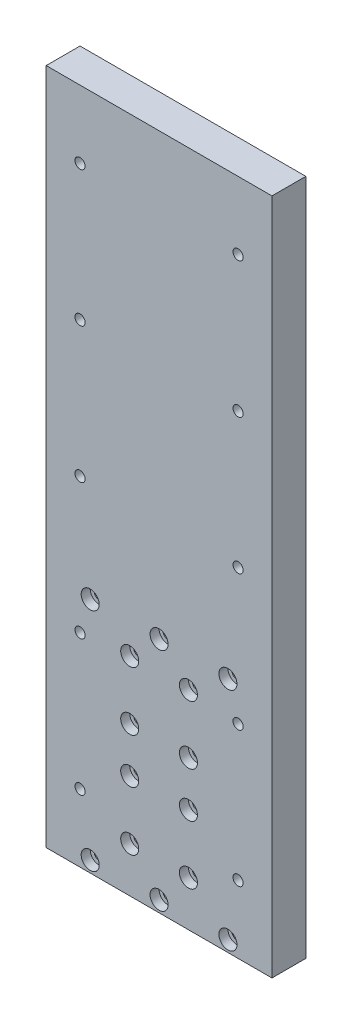
SolidWorks part; units mm, degrees
ref_plane "Piano frontale" through (0, 0, 0) normal (0, 0, 1) x (1, 0, 0)
ref_plane "Piano superiore" through (0, 0, 0) normal (0, 1, 0) x (1, 0, 0)
ref_plane "Piano destro" through (0, 0, 0) normal (1, 0, 0) x (0, 0, -1)
sketch "Schizzo1" plane through (0, 0, 0) normal (0, 0, 1) x (1, 0, 0)
  line L1 (0, 0) -> (100, 0)
  line L2 (0, 0) -> (0, 300)
  line L3 (0, 300) -> (100, 300)
  line L4 (100, 0) -> (100, 300)
  dimension "D1" = 100
  dimension "D2" = 300
extrude "Estrusione-Estrusione1" add sketch "Schizzo1" against normal blind 15
sketch "Schizzo2" plane through (0, 0, 0) normal (0, 0, 1) x (1, 0, 0)
  line L0 (0, 0) -> (104.4353, 0) construction
  line L1 (0, 5) -> (104.4353, 5) construction
  line L2 (23.1648, 20) -> (74.0129, 20) construction
  line L3 (23.1648, 46) -> (74.0129, 46) construction
  line L4 (23.1648, 66) -> (74.0129, 66) construction
  line L5 (23.1648, 92) -> (74.0129, 92) construction
  line L6 (6.7858, 105) -> (86.7249, 105) construction
  line L11 (0, 92) -> (144.5719, 92) construction
  line L12 (0, 66) -> (144.5719, 66) construction
  line L14 (50, 0) -> (50, 300) construction
  line L15 (0, 46) -> (144.5719, 46) construction
  line L17 (63, 0) -> (63, 105) construction
  line L19 (0, 20) -> (144.5719, 20) construction
  line L20 (0, 5) -> (144.5719, 5) construction
  line L21 (0, 0) -> (144.5719, 0) construction
  line L22 (0, 105) -> (144.5719, 105) construction
  line L23 (100, 300) -> (0, 300) construction
  circle A0 centre (19.5, 105) radius 2.25
  circle A1 centre (19.5, 5) radius 2.25
  circle A2 centre (37, 20) radius 2.25
  circle A3 centre (37, 46) radius 2.25
  circle A4 centre (37, 66) radius 2.25
  circle A5 centre (37, 92) radius 2.25
  circle A6 centre (50, 105) radius 2.25
  circle A7 centre (50, 5) radius 2.25
  circle A8 centre (63, 92) radius 2.25
  circle A9 centre (63, 66) radius 2.25
  circle A10 centre (63, 46) radius 2.25
  circle A11 centre (63, 20) radius 2.25
  circle A12 centre (80.5, 5) radius 2.25
  circle A13 centre (80.5, 105) radius 2.25
  dimension "D7" = 4.5
  dimension "D8" = 13
  dimension "D2" = 26
  dimension "D3" = 26
  dimension "D4" = 20
  dimension "D5" = 20
  dimension "D9" = 30.5
  dimension "D10" = 30.5
  dimension "D1" = 5
  dimension "D6" = 105
extrude "Taglio-Estrusione1" cut sketch "Schizzo2" against normal through all
sketch "Schizzo4" plane through (0, 0, 0) normal (0, 0, 1) x (1, 0, 0)
  circle A0 centre (19.5, 105) radius 4
  circle A1 centre (50, 105) radius 4
  circle A2 centre (80.5, 105) radius 4
  circle A3 centre (37, 92) radius 4
  circle A4 centre (63, 92) radius 4
  circle A5 centre (37, 66) radius 4
  circle A6 centre (63, 66) radius 4
  circle A7 centre (37, 46) radius 4
  circle A8 centre (63, 46) radius 4
  circle A9 centre (19.5, 5) radius 4
  circle A10 centre (37, 20) radius 4
  circle A11 centre (63, 20) radius 4
  circle A12 centre (50, 5) radius 4
  circle A13 centre (80.5, 5) radius 4
  dimension "D1" = 8
extrude "Taglio-Estrusione2" cut sketch "Schizzo4" against normal blind 4
sketch "Schizzo5" plane through (0, 0, 0) normal (0, 0, 1) x (1, 0, 0)
  line L0 (0, 150) -> (100, 150) construction
  line L1 (0, 300) -> (0, 0) construction
  line L2 (100, 0) -> (100, 300) construction
  line L3 (85, 300) -> (85, 0) construction
  line L4 (100, 300) -> (0, 300) construction
  line L5 (0, 0) -> (104.4353, 0) construction
  line L6 (50, 0) -> (50, 300) construction
  line L7 (50, 300) -> (50, 0) construction
  circle A0 centre (85, 150) radius 2
  circle A1 centre (85, 210) radius 2
  circle A2 centre (85, 270) radius 2
  circle A3 centre (85, 30) radius 2
  circle A4 centre (85, 90) radius 2
  circle A5 centre (15, 90) radius 2
  circle A6 centre (15, 30) radius 2
  circle A7 centre (15, 270) radius 2
  circle A8 centre (15, 210) radius 2
  circle A9 centre (15, 150) radius 2
  point P18 (85, 150)
  dimension "D1" = 4
  dimension "D2" = 35
  dimension "D3" = 3
extrude "Taglio-Estrusione3" cut sketch "Schizzo5" against normal through all
hole_wizard "Foro per Vite M4-1" positions "Schizzo3D1" profile "Schizzo6" hole size "M4" standard "Ansi Metric"
sketch3d "Schizzo3D1"
  line L0 (15, 270, -15) -> (15, 270, 0) construction
  line L1 (85, 270, -15) -> (85, 270, 0) construction
  line L2 (15, 210, -15) -> (15, 210, 0) construction
  line L3 (85, 210, -15) -> (85, 210, 0) construction
  line L4 (15, 150, -15) -> (15, 150, 0) construction
  line L5 (85, 150, -15) -> (85, 150, 0) construction
  line L6 (15, 90, -15) -> (15, 90, 0) construction
  line L7 (85, 90, -15) -> (85, 90, 0) construction
  line L8 (15, 30, -15) -> (15, 30, 0) construction
  line L9 (85, 30, -15) -> (85, 30, 0) construction
  point P0 (15, 270, 0)
  point P4 (85, 270, 0)
  point P8 (15, 210, 0)
  point P12 (85, 210, 0)
  point P16 (15, 150, 0)
  point P20 (85, 150, 0)
  point P24 (15, 90, 0)
  point P28 (85, 90, 0)
  point P33 (15, 30, 0)
  point P37 (85, 30, 0)
sketch "Schizzo6" plane through (15, 270, 0) normal (1, 0, 0) x (0, -1, 0)
  line L0 (0, 0) -> (0, 11.3519)
  line L1 (0, 11.3519) -> (2.25, 10)
  line L2 (2.25, 10) -> (2.25, 0)
  line L5 (2.25, 0) -> (0, 0)
  line L10 (0, 11.3519) -> (-2.25, 10) construction
  line L11 (0, -6.35) -> (0, 107.95) construction
  dimension "Hole Dia." = 4.5
  dimension "Hole Depth" = 10
  dimension "Drill Angle" = 118
